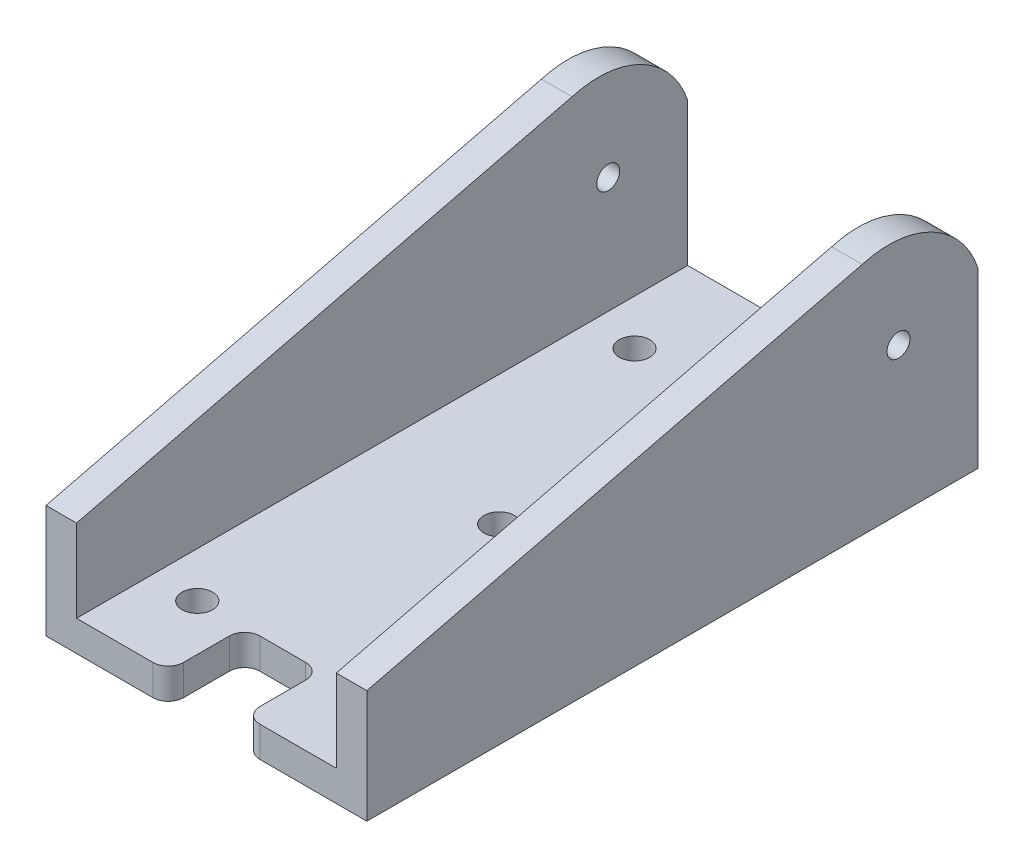
SolidWorks part; units mm, degrees
ref_plane "Front Plane" through (0, 0, 0) normal (0, 0, 1) x (1, 0, 0)
ref_plane "Top Plane" through (0, 0, 0) normal (0, 1, 0) x (1, 0, 0)
ref_plane "Right Plane" through (0, 0, 0) normal (1, 0, 0) x (0, 0, -1)
sketch "Sketch1" plane through (0, 0, 0) normal (0, 1, 0) x (1, 0, 0)
  line L1 (5.25, -10) -> (-5.25, -10)
  line L2 (5.25, -10) -> (5.25, 10)
  line L3 (5.25, 10) -> (-5.25, 10)
  line L4 (-5.25, -10) -> (-5.25, 10)
  line L5 (5.25, -10) -> (-5.25, 10) construction
  line L6 (5.25, 10) -> (-5.25, -10) construction
  point P0 (0, 0)
  dimension "D1" = 10.5
  dimension "D2" = 20
extrude "Boss-Extrude1" add sketch "Sketch1" along normal blind 10
shell "Shell2" thickness 1
sketch "Sketch2" plane through (0, 0, 0) normal (0, -1, 0) x (1, 0, 0)
  line L0 (-5.25, 10) -> (5.25, 10) construction
  line L1 (1.25, 10) -> (-1.25, 10)
  line L2 (1.25, 10) -> (1.25, 7.5)
  line L3 (1.25, 7.5) -> (-1.25, 7.5)
  line L4 (-1.25, 10) -> (-1.25, 7.5)
  line L5 (0, 0) -> (0, 50000) construction
  dimension "D1" = 2.5
  dimension "D2" = 1.25
  dimension "D3" = 2.5
extrude "Cut-Extrude1" cut sketch "Sketch2" against normal blind 1
sketch "Sketch3" plane through (0, 9, 0) normal (0, -1, 0) x (1, 0, 0)
  line L1 (-4.25, 10) -> (4.25, 10)
  line L2 (-4.25, 10) -> (-4.25, -9)
  line L3 (-4.25, -9) -> (4.25, -9)
  line L4 (4.25, 10) -> (4.25, -9)
extrude "Cut-Extrude2" cut sketch "Sketch3" against normal blind 1
sketch "Sketch4" plane through (-4.25, 0, 0) normal (-1, 0, 0) x (0, 0, 1)
  line L0 (10, 10) -> (10, 3.6995)
  line L1 (-10, 10) -> (-10, 0) construction
  line L2 (-6.2134, 7.6743) -> (10, 3.6995)
  line L6 (10, 10) -> (-10, 10)
  line L7 (-10, 10) -> (-10, 5.6761)
  line L8 (10, 10) -> (10, 0) construction
  line L9 (10, 10) -> (10, 1) construction
  arc A1 (-10, 5.6761) -> (-6.2134, 7.6743) centre (-7.0751, 4.7204) cw
  point P3 (9.25, 3.6995)
  point P4 (-6.2377, 7.5078)
extrude "Cut-Extrude3" cut sketch "Sketch4" against normal through all both and the other way through all
sketch "Sketch5" plane through (0, 0, -9) normal (0, 0, 1) x (1, 0, 0)
  line L1 (-4.25, 7.121) -> (4.25, 7.121)
  line L2 (-4.25, 7.121) -> (-4.25, 1)
  line L3 (-4.25, 1) -> (4.25, 1)
  line L4 (4.25, 7.121) -> (4.25, 1)
extrude "Cut-Extrude4" cut sketch "Sketch5" against normal blind 1
fillet "Fillet4" radius 0.5 4 edges at (-1.25, 0.5, 7.5) (-1.25, 0.5, 10) (1.25, 0.5, 10) (1.25, 0.5, 7.5)
sketch "Sketch10" plane through (-5.25, 0, 0) normal (-1, 0, 0) x (0, 0, 1)
  circle A0 centre (-7.3981, 4.7961) radius 0.375
  dimension "D1" = 0.75
extrude "Cut-Extrude9" cut sketch "Sketch10" against normal through all both and the other way through all
sketch "Sketch11" plane through (0, 1, 0) normal (0, 1, 0) x (1, 0, 0)
  line L0 (-2.767, 6.7769) -> (-2.767, -0.4188) construction
  line L1 (-2.767, -0.4188) -> (-2.767, -7.6145) construction
  line L2 (-2.767, -7.6145) -> (-4.25, -7.6145) construction
  line L3 (-4.25, -10) -> (-4.25, 6.2134) construction
  line L4 (-2.767, -0.4188) -> (0, -0.4188) construction
  line L5 (0, -0.4188) -> (2.767, -0.4188) construction
  line L6 (2.767, -0.4188) -> (2.767, 6.7769) construction
  line L7 (2.767, -0.4188) -> (2.767, -7.6145) construction
  line L8 (2.767, -7.6145) -> (4.25, -7.6145) construction
  line L9 (4.25, -10) -> (4.25, 10) construction
  circle A0 centre (0, -0.4188) radius 0.5
  circle A1 centre (2.767, -7.6145) radius 0.5
  circle A2 centre (-2.767, -7.5321) radius 0.5
  circle A3 centre (-2.767, 6.7769) radius 0.5
  circle A4 centre (2.767, 6.7769) radius 0.5
  dimension "D1" = 1
extrude "Cut-Extrude10" cut sketch "Sketch11" against normal through all both
